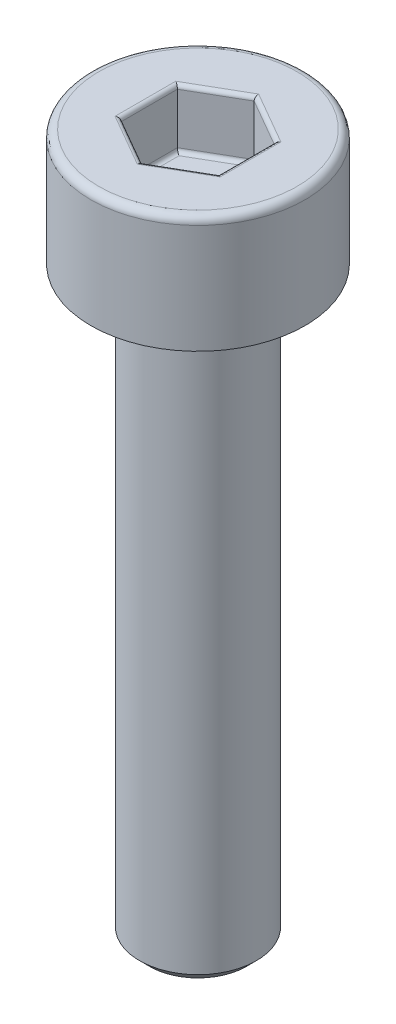
SolidWorks part; units mm, degrees
ref_plane "Front Plane" through (0, 0, 0) normal (0, 0, 1) x (1, 0, 0)
ref_plane "Top Plane" through (0, 0, 0) normal (0, 1, 0) x (1, 0, 0)
ref_plane "Right Plane" through (0, 0, 0) normal (1, 0, 0) x (0, 0, -1)
sketch "Sketch1" plane through (0, 0, 0) normal (0, 0, 1) x (1, 0, 0)
  line L0 (0, 0) -> (0, -47.0967) construction
  line L1 (0, -18) -> (-1.5, -18)
  line L2 (-1.5, -18) -> (-1.5, -3)
  line L3 (-1.5, -3) -> (-2.75, -3)
  line L4 (-2.75, -3) -> (-2.75, 0)
  line L5 (-2.75, 0) -> (0, 0)
  line L6 (0, 0) -> (0, -18)
  dimension "d" = 3
  dimension "l" = 18
  dimension "k" = 3
  dimension "dk" = 5.5
revolve "Revolve1" add sketch "Sketch1" angle 360 about L0
chamfer "Chamfer1" distance 0.25 angle 45 2 edges at (0, -3, 1.5) (0, -18, 1.5)
fillet "Fillet1" radius 0.2 1 edges at (0, 0, 2.75)
sketch "Sketch2" plane through (0, 0, 0) normal (0, 1, 0) x (1, 0, 0)
  line L1 (0, 1.4434) -> (-1.25, 0.7217)
  line L2 (-1.25, 0.7217) -> (-1.25, -0.7217)
  line L3 (-1.25, -0.7217) -> (0, -1.4434)
  line L4 (0, -1.4434) -> (1.25, -0.7217)
  line L5 (1.25, -0.7217) -> (1.25, 0.7217)
  line L6 (1.25, 0.7217) -> (0, 1.4434)
  circle A0 centre (0, 0) radius 1.25 construction
  dimension "s" = 2.5
extrude "Cut-Extrude1" cut sketch "Sketch2" against normal blind 1.5
fillet "Fillet2" radius 0.1 12 edges at (-0.625, 0, -1.0825) (-1.25, 0, 0) (-0.625, 0, 1.0825) (0.625, 0, 1.0825) (1.25, 0, 0) (0.625, 0, -1.0825) (1.25, -1.5, 0) (0.625, -1.5, 1.0825) (-0.625, -1.5, 1.0825) (-1.25, -1.5, 0) (-0.625, -1.5, -1.0825) (0.625, -1.5, -1.0825)
